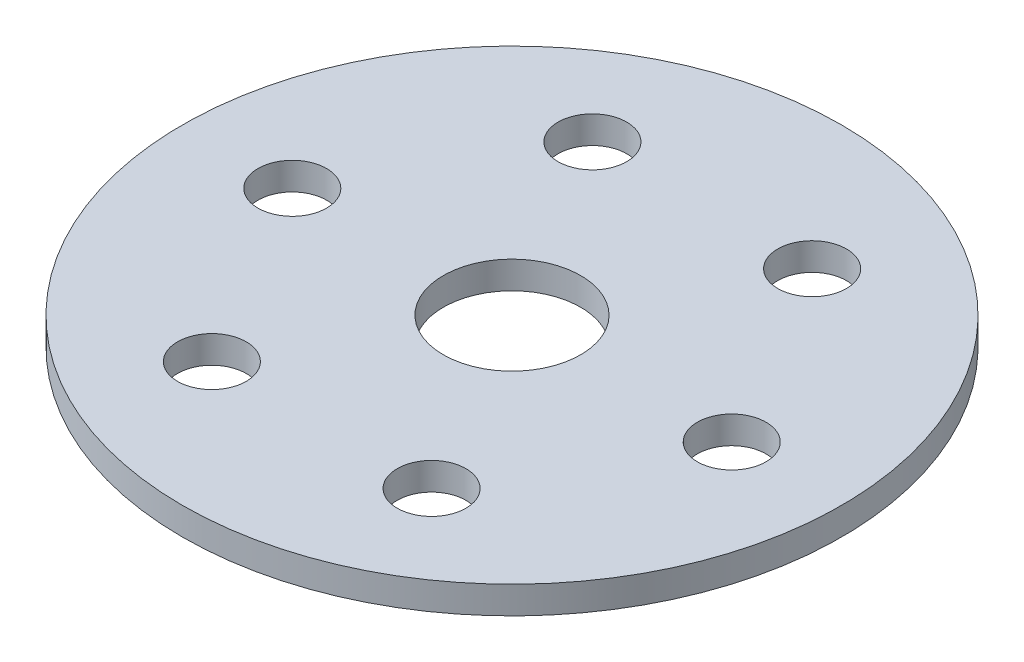
SolidWorks part; units mm, degrees
ref_plane "Front Plane" through (0, 0, 0) normal (0, 0, 1) x (1, 0, 0)
ref_plane "Top Plane" through (0, 0, 0) normal (0, 1, 0) x (1, 0, 0)
ref_plane "Right Plane" through (0, 0, 0) normal (1, 0, 0) x (0, 0, -1)
sketch "Sketch1" plane through (0, 0, 0) normal (0, 1, 0) x (1, 0, 0)
  circle A0 centre (0, 0) radius 76.2
  circle A1 centre (0, 0) radius 15.875
  dimension "D1" = 152.4
  dimension "D2" = 31.75
extrude "Plate extrude" add sketch "Sketch1" along normal blind 6.35
hole_wizard "5/8 (0.625) Diameter Hole1" positions "Sketch2" profile "Sketch3" hole size "5/8" standard "ANSI Inch" end condition through all
sketch "Sketch2" plane through (0, 6.35, 0) normal (0, 1, 0) x (1, 0, 0)
  line L0 (-3.4925, 0) -> (3.4925, 0) construction
  circle A2 centre (0, 0) radius 76.2 construction
  point P0 (-50.8, 0)
  dimension "D1" = 50.8
sketch "Sketch3" plane through (-50.8, 6.35, 0) normal (1, 0, 0) x (0, 0, 1)
  line L0 (0, 0) -> (0, 6.35)
  line L1 (0, 6.35) -> (7.9375, 6.35)
  line L2 (7.9375, 6.35) -> (7.9375, 0)
  line L5 (7.9375, 0) -> (0, 0)
  line L11 (0, -6.35) -> (0, 107.95) construction
  dimension "Thru Hole Dia." = 15.875
  dimension "Thru Hole Depth" = 6.35
pattern_circular "CirPattern1" count 6 over 360 about axis through (0, 0, 0) along (0, 1, 0) of "5/8 (0.625) Diameter Hole1"
